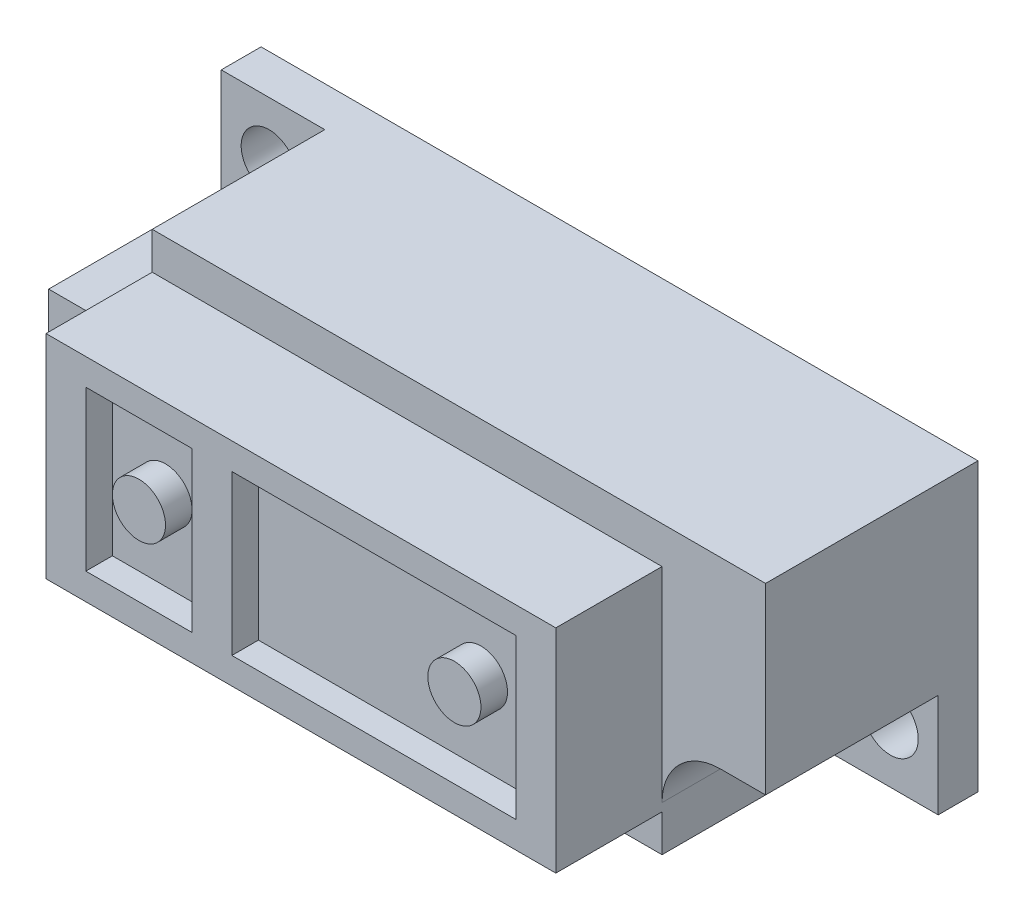
SolidWorks part; units mm, degrees
ref_plane "Front" through (0, 0, 0) normal (0, 0, 1) x (1, 0, 0)
ref_plane "Top" through (0, 0, 0) normal (0, 1, 0) x (1, 0, 0)
ref_plane "Right" through (0, 0, 0) normal (1, 0, 0) x (0, 0, -1)
sketch "Esquisse1" plane through (0, 0, 0) normal (0, 0, 1) x (1, 0, 0)
  line L1 (-13.5, -5.4) -> (13.5, -5.4)
  line L2 (-13.5, -5.4) -> (-13.5, 5.4)
  line L3 (-13.5, 5.4) -> (13.5, 5.4)
  line L4 (13.5, -5.4) -> (13.5, 5.4)
  line L5 (-13.5, -5.4) -> (13.5, 5.4) construction
  line L6 (-13.5, 5.4) -> (13.5, -5.4) construction
  point P0 (0, 0)
  dimension "D1" = 10.8
  dimension "D2" = 27
extrude "Boss.-Extru.1" add sketch "Esquisse1" along normal blind 8
sketch "Esquisse2" plane through (0, 0, 8) normal (0, 0, 1) x (1, 0, 0)
  line L0 (-11.7, 5.4) -> (-11.7, 3.3) construction
  line L1 (13.5, 5.4) -> (-13.5, 5.4) construction
  line L2 (-11.7, 3.3) -> (-13.5, 3.3) construction
  line L3 (-13.5, 5.4) -> (-13.5, -5.4) construction
  line L4 (11.7, -3.3) -> (11.7, -5.4) construction
  line L5 (-13.5, -5.4) -> (13.5, -5.4) construction
  line L6 (11.7, -3.3) -> (13.5, -3.3) construction
  line L7 (13.5, -5.4) -> (13.5, 5.4) construction
  circle A0 centre (-11.7, 3.3) radius 1.05
  circle A1 centre (11.7, -3.3) radius 1.05
  dimension "D1" = 2.1
  dimension "D2" = 2.1
  dimension "D3" = 23.4
extrude "Enlèv. mat.-Extru.1" cut sketch "Esquisse2" against normal through all
sketch "Esquisse3" plane through (0, 0, 8) normal (0, 0, 1) x (1, 0, 0)
  line L1 (-9.6, -4) -> (9.6, -4)
  line L2 (-9.6, -4) -> (-9.6, 4)
  line L3 (-9.6, 4) -> (9.6, 4)
  line L4 (9.6, -4) -> (9.6, 4)
  line L5 (-9.6, -4) -> (9.6, 4) construction
  line L6 (-9.6, 4) -> (9.6, -4) construction
  point P0 (0, 0)
  dimension "D1" = 19.2
  dimension "D2" = 8
extrude "Boss.-Extru.2" add sketch "Esquisse3" along normal blind 4
sketch "Esquisse4" plane through (0, 0, 8) normal (0, 0, 1) x (1, 0, 0)
  line L0 (-9.6, 4) -> (-9.6, -4) construction
  line L1 (-9.6, 3.7) -> (-9.6, 5.4)
  line L2 (13.5, 5.4) -> (-13.5, 5.4) construction
  line L3 (-9.6, 5.4) -> (-13.5, 5.4)
  line L4 (-13.5, 5.4) -> (-13.5, 1.5)
  line L5 (-13.5, 5.4) -> (-13.5, -5.4) construction
  line L6 (-13.5, 1.5) -> (-11.8, 1.5)
  line L7 (9.6, -5.4) -> (13.5, -5.4)
  line L8 (-13.5, -5.4) -> (13.5, -5.4) construction
  line L9 (13.5, -5.4) -> (13.5, -1.5)
  line L10 (13.5, -5.4) -> (13.5, 5.4) construction
  line L11 (13.5, -1.5) -> (11.8, -1.5)
  line L12 (9.6, -3.7) -> (9.6, -5.4)
  line L13 (9.6, -4) -> (9.6, 4) construction
  arc A0 (-11.8, 1.5) -> (-9.6, 3.7) centre (-11.8, 3.7) ccw
  arc A1 (11.8, -1.5) -> (9.6, -3.7) centre (11.8, -3.7) ccw
  dimension "D2" = 2.2
  dimension "D1" = 2.2
extrude "Enlèv. mat.-Extru.2" cut sketch "Esquisse4" against normal blind 6.5
sketch "Esquisse5" plane through (0, 0, 12) normal (0, 0, 1) x (1, 0, 0)
  line L0 (-6.1, 3) -> (-6.1, 0) construction
  line L1 (-8.1, 3) -> (-4.1, 3)
  line L2 (-8.1, 3) -> (-8.1, -3)
  line L3 (-8.1, -3) -> (-4.1, -3)
  line L4 (-4.1, 3) -> (-4.1, -3)
  line L5 (-2.6, 3) -> (8.1, 3)
  line L6 (-2.6, 3) -> (-2.6, -3)
  line L7 (-2.6, -3) -> (8.1, -3)
  line L8 (8.1, 3) -> (8.1, -3)
  line L9 (-6.1, 0) -> (-4.1, 0) construction
  line L10 (-4.1, 0) -> (-2.6, 0) construction
  line L11 (-2.6, 0) -> (5.78, 0) construction
  line L12 (9.6, -4) -> (9.6, 4) construction
  line L13 (-6.1, 0) -> (-9.6, 0) construction
  line L14 (-9.6, 4) -> (-9.6, -4) construction
  circle A0 centre (5.78, 0) radius 1
  circle A1 centre (-6.1, 0) radius 1
  dimension "D7" = 2
  dimension "D8" = 2
  dimension "D1" = 11.88
  dimension "D2" = 6
  dimension "D3" = 4
  dimension "D4" = 1.5
  dimension "D5" = 1.5
  dimension "D6" = 1.5
extrude "Enlèv. mat.-Extru.3" cut sketch "Esquisse5" against normal blind 1
sketch "Esquisse6" plane through (0, 0, 8) normal (0, 0, 1) x (1, 0, 0)
  line L0 (-9.6, -4) -> (9.6, -4) construction
  line L1 (-13.5, -5.4) -> (-3.65, -5.4)
  line L2 (-13.5, -5.4) -> (-13.5, -4)
  line L3 (-13.5, -4) -> (-3.65, -4)
  line L4 (-3.65, -5.4) -> (-3.65, -4)
  dimension "D1" = 9.85
extrude "Enlèv. mat.-Extru.4" cut sketch "Esquisse6" against normal through all
sketch "Esquisse7" plane through (0, -4, 0) normal (0, -1, 0) x (1, 0, 0)
  line L0 (-8.575, 0) -> (-8.575, -3) construction
  line L1 (-11.575, 3) -> (-5.575, 3)
  line L2 (-11.575, 3) -> (-11.575, -3)
  line L3 (-11.575, -3) -> (-5.575, -3)
  line L4 (-5.575, 3) -> (-5.575, -3)
  line L5 (-3.65, 0) -> (-13.5, 0) construction
  dimension "D1" = 6
  dimension "D2" = 3
  dimension "D3" = 6
extrude "Boss.-Extru.3" add sketch "Esquisse7" along normal blind 3.5
sketch "Esquisse8" plane through (0, 0, -3) normal (0, 0, -1) x (-1, 0, 0)
  line L0 (8.575, -7.5) -> (8.575, -5.75) construction
  line L1 (11.075, -4.5) -> (6.075, -4.5)
  line L2 (11.075, -4.5) -> (11.075, -7)
  line L3 (11.075, -7) -> (6.075, -7)
  line L4 (6.075, -4.5) -> (6.075, -7)
  line L5 (11.075, -4.5) -> (6.075, -7) construction
  line L6 (11.075, -7) -> (6.075, -4.5) construction
  line L7 (11.575, -7.5) -> (5.575, -7.5) construction
  line L8 (8.575, -5.75) -> (11.575, -5.75) construction
  line L9 (11.575, -7.5) -> (11.575, -4) construction
  point P0 (8.575, -5.75)
  dimension "D1" = 0.5
  dimension "D2" = 0.5
extrude "Enlèv. mat.-Extru.5" cut sketch "Esquisse8" against normal blind 3.5
sketch "Esquisse9" plane through (0, 0, 0) normal (0, 0, -1) x (-1, 0, 0)
  line L0 (9, 4.9) -> (-13, 4.9)
  line L1 (-13, 4.9) -> (-13, -0.9)
  line L2 (13, 0.9) -> (13, -4)
  line L4 (13, -4) -> (3.65, -4)
  line L5 (3.65, -4) -> (3.65, -4.9)
  line L6 (3.65, -4.9) -> (-9, -4.9)
  line L7 (3.65, -5.4) -> (-13.5, -5.4) construction
  line L8 (-13.5, 5.4) -> (13.5, 5.4) construction
  line L9 (-13.5, -5.4) -> (-13.5, 5.4) construction
  line L11 (13.5, 5.4) -> (13.5, -4) construction
  line L12 (3.65, -5.4) -> (3.65, -4) construction
  line L13 (13, 0.9) -> (13, 4.9) construction
  line L14 (13, 4.9) -> (9, 4.9) construction
  line L15 (-9, -4.9) -> (-13, -4.9) construction
  line L16 (-13, -4.9) -> (-13, -0.9) construction
  arc A0 (-9, -4.9) -> (-13, -0.9) centre (-13, -4.9) ccw
  arc A1 (9, 4.9) -> (13, 0.9) centre (13, 4.9) ccw
  dimension "D5" = 4
  dimension "D1" = 0.5
  dimension "D2" = 0.5
  dimension "D3" = 0.5
  dimension "D4" = 0.5
extrude "Enlèv. mat.-Extru.6" cut sketch "Esquisse9" against normal blind 2
